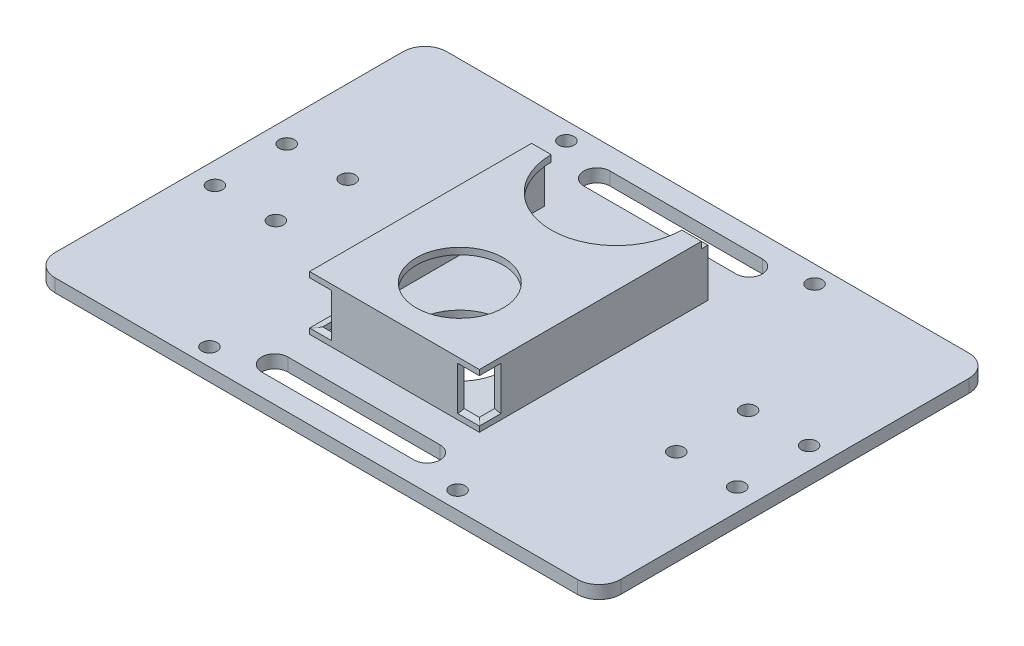
SolidWorks part; units mm, degrees
ref_plane "前视基准面" through (0, 0, 0) normal (0, 0, 1) x (1, 0, 0)
ref_plane "上视基准面" through (0, 0, 0) normal (0, 1, 0) x (1, 0, 0)
ref_plane "右视基准面" through (0, 0, 0) normal (1, 0, 0) x (0, 0, -1)
sketch "草图1" plane through (0, 0, 0) normal (0, 1, 0) x (1, 0, 0)
  line L0 (0, 0) -> (65, 0) construction
  line L1 (-60, 45) -> (60, 45)
  line L2 (-65, 40) -> (-65, -40)
  line L3 (-60, -45) -> (60, -45)
  line L4 (65, 40) -> (65, -40)
  line L5 (0, 0) -> (0, 50.1075) construction
  arc A0 (-65, -40) -> (-60, -45) centre (-60, -40) ccw
  arc A1 (60, -45) -> (65, -40) centre (60, -40) ccw
  arc A2 (65, 40) -> (60, 45) centre (60, 40) ccw
  arc A3 (-60, 45) -> (-65, 40) centre (-60, 40) ccw
  circle A4 centre (-60, 8.25) radius 1.75
  circle A5 centre (-46, 8.25) radius 1.75
  circle A6 centre (-46, -8.25) radius 1.75
  circle A7 centre (-60, -8.25) radius 1.75
  circle A8 centre (60, 8.25) radius 1.75
  circle A9 centre (60, -8.25) radius 1.75
  circle A10 centre (46, -8.25) radius 1.75
  circle A11 centre (46, 8.25) radius 1.75
  circle A12 centre (-28.5, 41) radius 1.75
  circle A13 centre (-28.5, -41) radius 1.75
  circle A14 centre (28.5, -41) radius 1.75
  circle A15 centre (28.5, 41) radius 1.75
  point P0 (0, 0)
  dimension "D3" = 5
  dimension "D6" = 3.5
  dimension "D10" = 3.5
  dimension "D11" = 3.5
  dimension "D1" = 65
  dimension "D2" = 45
  dimension "D4" = 120
  dimension "D5" = 80
  dimension "D7" = 5
  dimension "D8" = 8.25
  dimension "D9" = 14
  dimension "D12" = 28.5
  dimension "D13" = 41
extrude "凸台-拉伸1" add sketch "草图1" along normal blind 3
sketch "草图2" plane through (0, 3, 0) normal (0, 1, 0) x (1, 0, 0)
  line L0 (-18, 25.5) -> (-19.5, 25.5)
  line L1 (-18, 25.5) -> (18, 25.5)
  line L2 (-18, 25.5) -> (-18, -25.5)
  line L3 (-18, -25.5) -> (18, -25.5)
  line L4 (18, 25.5) -> (18, -25.5)
  line L5 (-18, 25.5) -> (18, -25.5) construction
  line L6 (-18, -25.5) -> (18, 25.5) construction
  line L8 (-19.5, 25.5) -> (-19.5, -27)
  line L9 (-19.5, -27) -> (19.5, -27)
  line L10 (19.5, 25.5) -> (19.5, -27)
  line L11 (-18.4167, 25.5) -> (19.5, -27) construction
  line L12 (-19.5, -27) -> (18.4167, 25.5) construction
  line L13 (18, 25.5) -> (19.5, 25.5)
  point P0 (0, 0)
  point P6 (0, 0)
  dimension "D1" = 51
  dimension "D2" = 36
  dimension "D3" = 1.5
  dimension "D4" = 1.5
extrude "凸台-拉伸2" add sketch "草图2" along normal blind 11 contours L13 L4 L3 L2 L0 L8 L9 L10
sketch "草图3" plane through (0, 14, 0) normal (0, 1, 0) x (1, 0, 0)
  line L0 (-19.5, 24) -> (19.5, 24)
  line L2 (-19.5, 24) -> (-19.5, -27)
  line L3 (-19.5, -27) -> (19.5, -27)
  line L4 (19.5, 24) -> (19.5, -27)
  line L5 (-17.3333, 24) -> (19.5, -27) construction
  line L6 (-19.5, -27) -> (17.3333, 24) construction
  circle A0 centre (0, 24) radius 15
  point P0 (0, 0)
  line M6 (18, 25.5) -> (18, -25.5)
  line M7 (18, -25.5) -> (-18, -25.5)
  line M8 (-18, -25.5) -> (-18, 25.5)
  line M10 (-19.5, 25.5) -> (-19.5, -27)
  line M11 (-19.5, -27) -> (19.5, -27)
  line M12 (19.5, -27) -> (19.5, 25.5)
  dimension "D1" = 30
extrude "凸台-拉伸3" add sketch "草图3" along normal blind 1.5 contours A0 L0 M8 M7 M6 | L0 M10 M11 M12 M6 M7 M8
sketch "草图5" plane through (0, 15.5, 0) normal (0, 1, 0) x (1, 0, 0)
  line L0 (19.5, 25.5) -> (19.5, -27) construction
  circle A0 centre (0, -12) radius 10
  dimension "D1" = 20
  dimension "D2" = 12
  dimension "D3" = 19.5
extrude "切除-拉伸1" cut sketch "草图5" against normal through all
sketch "草图6" plane through (19.5, 0, 0) normal (1, 0, 0) x (0, 0, -1)
  line L0 (-27, 15.5) -> (-27, 3) construction
  circle A0 centre (-27, 9.25) radius 5
  dimension "D1" = 10
extrude "切除-拉伸2" cut sketch "草图6" against normal blind 5
sketch "草图7" plane through (0, 0, 27) normal (0, 0, 1) x (1, 0, 0)
  line L0 (19.5, 4.25) -> (19.5, 14.25) construction
  circle A0 centre (19.5, 9.25) radius 5
  dimension "D1" = 10
extrude "切除-拉伸3" cut sketch "草图7" against normal blind 5
mirror "镜向1" about plane through (0, 0, 0) normal (1, 0, 0) of "切除-拉伸2", "切除-拉伸3"
sketch "草图8" plane through (0, 3, 0) normal (0, 1, 0) x (1, 0, 0)
  line L0 (-17.5, -37) -> (17.5, -37) construction
  line L1 (-17.5, -34) -> (17.5, -34)
  line L2 (-17.5, -40) -> (17.5, -40)
  line L3 (-60, -45) -> (60, -45) construction
  arc A0 (-17.5, -34) -> (-17.5, -40) centre (-17.5, -37) ccw
  arc A1 (17.5, -40) -> (17.5, -34) centre (17.5, -37) ccw
  point P2 (0, -37)
  dimension "D2" = 3
  dimension "D1" = 35
  dimension "D3" = 8
extrude "切除-拉伸4" cut sketch "草图8" against normal blind 3
mirror "镜向2" about plane through (0, 0, 0) normal (0, 0, 1) of "切除-拉伸4"
